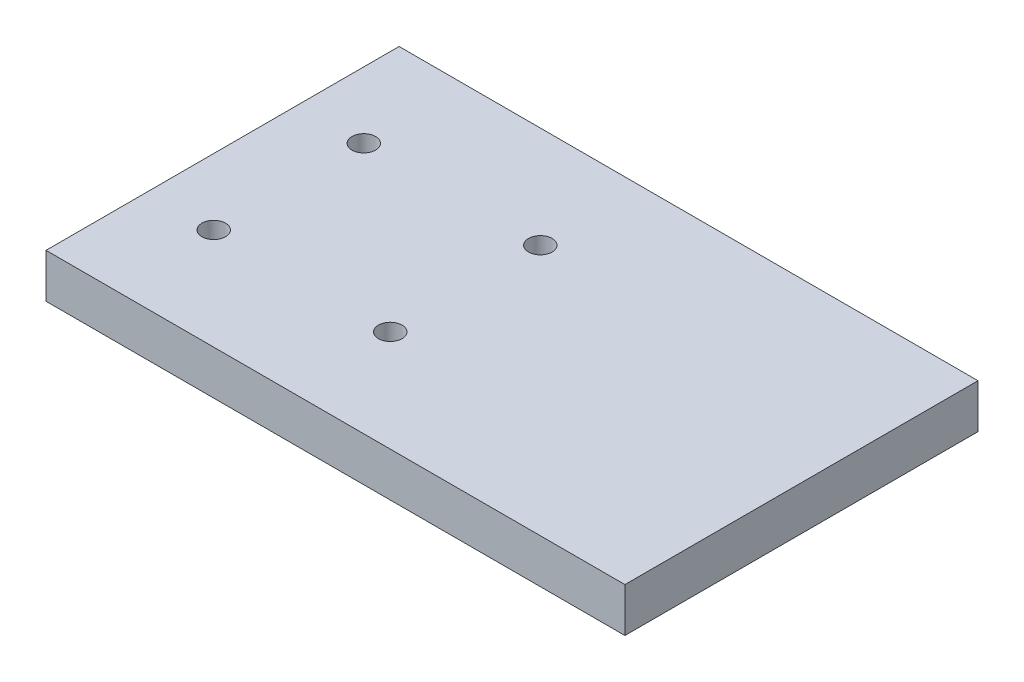
SolidWorks part; units mm, degrees
material "Acrylic (Medium-high impact)"
ref_plane "Front Plane" through (0, 0, 0) normal (0, 0, 1) x (1, 0, 0)
ref_plane "Top Plane" through (0, 0, 0) normal (0, 1, 0) x (1, 0, 0)
ref_plane "Right Plane" through (0, 0, 0) normal (1, 0, 0) x (0, 0, -1)
sketch "Sketch1" plane through (0, 0, 0) normal (0, 1, 0) x (1, 0, 0)
  line L0 (-25.2332, -25.4) -> (-6.5901, -25.4)
  line L1 (-6.5901, 25.4) -> (0.0612, 25.4)
  line L2 (-41.5846, 25.4) -> (-41.5846, -25.4)
  line L3 (-32.0584, 10.795) -> (-6.6584, 10.795) construction
  line L4 (-32.0584, 10.795) -> (-32.0584, -10.795) construction
  line L5 (-32.0584, -10.795) -> (-6.6584, -10.795) construction
  line L6 (0.0612, 25.4) -> (6.7125, 25.4)
  line L7 (-6.5901, -25.4) -> (6.7125, -25.4)
  line L10 (41.707, 25.4) -> (41.707, -25.4)
  line L12 (-41.5846, -25.4) -> (-38.5358, -25.4)
  line L13 (41.707, -25.4) -> (-41.5846, -25.4) construction
  line L14 (-38.5358, -25.4) -> (-38.5358, -33.8976) construction
  line L15 (41.707, 25.4) -> (-41.5846, 25.4) construction
  line L16 (-25.2332, 25.4) -> (0.0612, 25.4) construction
  line L17 (0.0612, 25.4) -> (25.3557, 25.4) construction
  line L45 (-25.2332, -33.8976) -> (-25.2332, -25.4) construction
  line L46 (25.3557, -25.4) -> (25.3557, -33.8976) construction
  line L47 (-25.2332, -25.4) -> (25.3557, -25.4) construction
  line L49 (41.707, -25.4) -> (38.6582, -25.4)
  line L50 (38.6582, -33.8976) -> (38.6582, -25.4) construction
  line L51 (-38.5358, 25.4) -> (-38.5358, 33.8976) construction
  line L52 (-38.5358, 33.8976) -> (-25.2332, 33.8976) construction
  line L53 (-25.2332, 33.8976) -> (-25.2332, 25.4) construction
  line L56 (25.3557, 33.8976) -> (25.3557, 25.4) construction
  line L60 (25.3557, 33.8976) -> (38.6582, 33.8976) construction
  line L61 (38.6582, 25.4) -> (38.6582, 33.8976) construction
  line L63 (25.3557, -33.8976) -> (38.6582, -33.8976) construction
  line L66 (-31.8845, 29.8145) -> (-31.8845, 33.8976) construction
  line L67 (32.0069, 29.8145) -> (32.0069, 33.8976) construction
  line L69 (6.7125, -25.4) -> (25.3557, -25.4)
  line L72 (-38.5358, -33.8976) -> (-25.2332, -33.8976) construction
  line L73 (-25.2332, 25.4) -> (-6.5901, 25.4)
  line L74 (-38.5358, 25.4) -> (-25.2332, 25.4)
  line L77 (41.707, 25.4) -> (38.6582, 25.4)
  line L81 (6.7125, 25.4) -> (25.3557, 25.4)
  line L84 (25.3557, 25.4) -> (38.6582, 25.4)
  line L85 (-41.5846, 25.4) -> (-38.5358, 25.4)
  line L87 (38.6582, -25.4) -> (25.3557, -25.4)
  line L88 (-25.2332, -25.4) -> (-38.5358, -25.4)
  line L94 (-31.8845, -33.8976) -> (-31.8845, -29.8145) construction
  line L95 (32.0069, -33.8976) -> (32.0069, -29.8145) construction
  circle A0 centre (-32.0584, 10.795) radius 1.7005
  circle A1 centre (-32.0584, -10.795) radius 1.7005
  circle A2 centre (-6.6584, -10.795) radius 1.7005
  circle A3 centre (-6.6584, 10.795) radius 1.7005
  circle A4 centre (-31.8845, -29.8145) radius 1.7005 construction
  circle A5 centre (32.0069, -29.8145) radius 1.7005 construction
  circle A6 centre (32.0069, 29.8145) radius 1.7005 construction
  circle A7 centre (-31.8845, 29.8145) radius 1.7005 construction
  point P16 (-32.0584, 0)
  dimension "D7" = 25.4
  dimension "D16" = 8.4976
  dimension "D9" = 25.3557
  dimension "D5" = 3.4011
  dimension "D3" = 83.2917
  dimension "D4" = 21.59
  dimension "D6" = 0.0612
  dimension "D8" = 6.7125
  dimension "D10" = 29.8145
  dimension "D11" = 25.4
  dimension "D14" = 6.6584
  dimension "D20" = 25.4
extrude "Boss-Extrude1" add sketch "Sketch1" along normal blind 6.35
